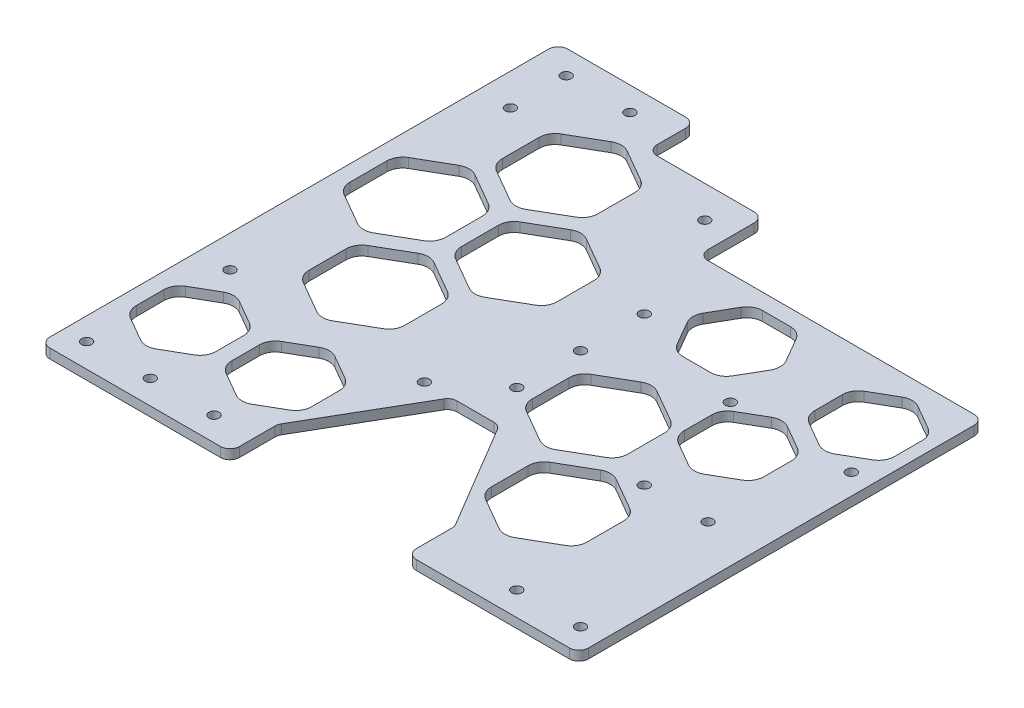
SolidWorks part; units mm, degrees
material "轻木"
ref_plane "前视基准面" through (0, 0, 0) normal (0, 0, 1) x (1, 0, 0)
ref_plane "上视基准面" through (0, 0, 0) normal (0, 1, 0) x (1, 0, 0)
ref_plane "右视基准面" through (0, 0, 0) normal (1, 0, 0) x (0, 0, -1)
other "Configuration Table"
sketch "草图1" plane through (0, 0, 0) normal (0, 1, 0) x (1, 0, 0)
  line L0 (7.5, 83.5) -> (7.5, 0) construction
  line L1 (0, 0) -> (15, 0) construction
  line L2 (0, 0) -> (0, 83.5) construction
  line L3 (0, 83.5) -> (15, 83.5) construction
  line L4 (15, 0) -> (15, 83.5) construction
  line L5 (7.5, 16) -> (7.5, 36) construction
  line L6 (0, 0) -> (0, 101) construction
  line L7 (0, 108.5) -> (-79.5, 108.5) construction
  line L8 (0, 101) -> (-79.5, 101) construction
  line L9 (0, 101) -> (0, 116) construction
  line L10 (0, 116) -> (-79.5, 116) construction
  line L11 (-79.5, 101) -> (-79.5, 116) construction
  line L12 (-33.5, 116) -> (-33.5, 101) construction
  line L13 (-36.5, 116) -> (-36.5, 101)
  line L14 (-36.5, 101) -> (0, 101)
  line L15 (0, 101) -> (0, 80.5)
  line L16 (0, 80.5) -> (15, 80.5)
  line L17 (15, 3) -> (0, 3)
  line L18 (15, 80.5) -> (45, 80.5)
  line L19 (92.5, -39) -> (0, -39) construction
  line L24 (0, 0) -> (15, 0) construction
  line L25 (0, 0) -> (0, -31.5) construction
  line L26 (0, -31.5) -> (15, -31.5) construction
  line L27 (15, 0) -> (15, -31.5) construction
  line L28 (0, -31.5) -> (92.5, -31.5) construction
  line L29 (0, -31.5) -> (0, -46.5) construction
  line L30 (0, -46.5) -> (92.5, -46.5) construction
  line L31 (92.5, -31.5) -> (92.5, -46.5) construction
  line L32 (7.5, 0) -> (7.5, -31.5) construction
  line L33 (32.5, -31.5) -> (32.5, -46.5) construction
  line L34 (35.5, -31.5) -> (35.5, -46.5)
  line L35 (89.5, -31.5) -> (89.5, -46.5)
  line L36 (89.5, -46.5) -> (35.5, -46.5)
  line L37 (15, 3) -> (35.5, -31.5)
  line L38 (89.5, -31.5) -> (89.5, 53.5)
  line L39 (89.5, 53.5) -> (155, 53.5) construction
  line L40 (-36.5, 116) -> (-79.5, 116)
  line L41 (55, 185.5) -> (142, 185.5) construction
  line L42 (55, 185.5) -> (55, 63.5) construction
  line L43 (55, 63.5) -> (142, 63.5) construction
  line L44 (142, 185.5) -> (142, 63.5) construction
  line L45 (55, 185.5) -> (142, 63.5) construction
  line L46 (55, 63.5) -> (142, 185.5) construction
  line L47 (-79.5, 116) -> (-79.5, 101)
  line L48 (-117.5, -39) -> (0, -39) construction
  line L49 (0, -31.5) -> (-117.5, -31.5) construction
  line L50 (0, -31.5) -> (0, -46.5) construction
  line L51 (0, -46.5) -> (-117.5, -46.5) construction
  line L52 (-117.5, -31.5) -> (-117.5, -46.5) construction
  line L53 (-17, -31.5) -> (-17, -46.5) construction
  line L54 (-32.5, -39) -> (-52.5, -39) construction
  line L55 (-79.5, 101) -> (-79.5, -46.5)
  line L56 (-79.5, -46.5) -> (-20, -46.5)
  line L57 (-20, -46.5) -> (-20, -31.5)
  line L58 (-20, -31.5) -> (0, 3)
  line L59 (45, 80.5) -> (45, 195.5) construction
  line L60 (45, 195.5) -> (155, 195.5) construction
  line L61 (155, 195.5) -> (155, 53.5) construction
  line L62 (61, 41.5) -> (61, 21.5) construction
  line L63 (-69.5, 91) -> (-8.5, 91) construction
  line L64 (-69.5, 91) -> (-69.5, 3) construction
  line L65 (-69.5, 3) -> (-8.5, 3) construction
  line L66 (-8.5, 91) -> (-8.5, 3) construction
  line L67 (-69.5, 91) -> (-8.5, 3) construction
  line L68 (-69.5, 3) -> (-8.5, 91) construction
  line L69 (61, 21.5) -> (25, 12.5) construction
  line L70 (25, 12.5) -> (25, 50.5) construction
  line L71 (25, 50.5) -> (61, 41.5) construction
  line L72 (89.5, 53.5) -> (89.5, 80.5)
  line L73 (89.5, 80.5) -> (45, 80.5)
  line L74 (45, 45.5) -> (54, 9.5) construction
  line L75 (54, 9.5) -> (74, 9.5) construction
  line L76 (74, 9.5) -> (83, 45.5) construction
  line L77 (83, 45.5) -> (45, 45.5) construction
  circle A0 centre (7.5, 16) radius 1.6
  circle A1 centre (7.5, 36) radius 1.6
  circle A2 centre (7.5, 56) radius 1.6
  circle A3 centre (-49.5, 108.5) radius 1.6
  circle A4 centre (-69.5, 108.5) radius 1.6
  circle A5 centre (82.5, -39) radius 1.6
  circle A6 centre (62.5, -39) radius 1.6
  circle A7 centre (-32.5, -39) radius 1.6
  circle A8 centre (-52.5, -39) radius 1.6
  circle A9 centre (-72.5, -39) radius 1.6
  circle A10 centre (-92.5, -39) radius 1.6 construction
  circle A11 centre (-112.5, -39) radius 1.6 construction
  circle A12 centre (55, 185.5) radius 1.6 construction
  circle A13 centre (142, 185.5) radius 1.6 construction
  circle A14 centre (142, 63.5) radius 1.6 construction
  circle A15 centre (55, 63.5) radius 1.6 construction
  circle A16 centre (-69.5, 91) radius 1.6
  circle A17 centre (-8.5, 91) radius 1.6
  circle A18 centre (-8.5, 3) radius 1.6
  circle A19 centre (-69.5, 3) radius 1.6
  circle A20 centre (25, 50.5) radius 1.6 construction
  circle A21 centre (61, 41.5) radius 1.6 construction
  circle A22 centre (61, 21.5) radius 1.6 construction
  circle A23 centre (25, 12.5) radius 1.6 construction
  circle A24 centre (83, 45.5) radius 1.6
  circle A25 centre (74, 9.5) radius 1.6
  circle A26 centre (54, 9.5) radius 1.6
  circle A27 centre (45, 45.5) radius 1.6
  point P53 (98.5, 124.5)
  point P85 (-39, 47)
  dimension "D3" = 16
  dimension "D6" = 3.2
  dimension "D10" = 20
  dimension "D11" = 16
  dimension "D20" = 20
  dimension "D21" = 10
  dimension "D27" = 17
  dimension "D28" = 32.5
  dimension "D1" = 15
  dimension "D2" = 83.5
  dimension "D5" = 20
  dimension "D7" = 101
  dimension "D8" = 15
  dimension "D9" = 33.5
  dimension "D12" = 10
  dimension "D13" = 3
  dimension "D14" = 3
  dimension "D15" = 3
  dimension "D16" = 46.5
  dimension "D17" = 92.5
  dimension "D18" = 17.5
  dimension "D19" = 3
  dimension "D22" = 3
  dimension "D23" = 85
  dimension "D24" = 30
  dimension "D25" = 122
  dimension "D26" = 87
  dimension "D30" = 20
  dimension "D31" = 5
  dimension "D32" = 3
  dimension "D33" = 10
  dimension "D34" = 10
  dimension "D35" = 110
  dimension "D36" = 10
  dimension "D37" = 61
  dimension "D38" = 88
  dimension "D39" = 10
  dimension "D40" = 10
  dimension "D41" = 36
  dimension "D42" = 20
  dimension "D43" = 38
  dimension "D44" = 10
  dimension "D45" = 30
  dimension "D46" = 38
  dimension "D47" = 36
  dimension "D48" = 20
  dimension "D49" = 35
  dimension "D4" = 3
  dimension "D29" = 5
extrude "凸台-拉伸1" add sketch "草图1" along normal blind 3
sketch "草图3" plane through (0, 3, 0) normal (0, 1, 0) x (1, 0, 0)
  line L1 (-112, 64.4327) -> (-97, 73.0929) construction
  line L2 (-97, 73.0929) -> (-97, 90.4134) construction
  line L3 (-97, 90.4134) -> (-112, 99.0737) construction
  line L4 (-112, 99.0737) -> (-127, 90.4134) construction
  line L5 (-127, 90.4134) -> (-127, 73.0929) construction
  line L6 (-127, 73.0929) -> (-112, 64.4327) construction
  line L8 (-112, 81.7532) -> (-104.5, 68.7628) construction
  line L9 (-77, 64.4327) -> (-62, 73.0929) construction
  line L10 (-62, 73.0929) -> (-62, 90.4134) construction
  line L11 (-62, 90.4134) -> (-77, 99.0737) construction
  line L12 (-77, 99.0737) -> (-92, 90.4134) construction
  line L13 (-92, 90.4134) -> (-92, 73.0929) construction
  line L14 (-92, 73.0929) -> (-77, 64.4327) construction
  line L15 (-42, 64.4327) -> (-27, 73.0929)
  line L16 (-27, 73.0929) -> (-27, 90.4134)
  line L17 (-27, 90.4134) -> (-42, 99.0737)
  line L18 (-42, 99.0737) -> (-57, 90.4134)
  line L19 (-57, 90.4134) -> (-57, 73.0929)
  line L20 (-57, 73.0929) -> (-42, 64.4327)
  line L21 (-7, 64.4327) -> (8, 73.0929) construction
  line L22 (8, 73.0929) -> (8, 90.4134) construction
  line L23 (8, 90.4134) -> (-7, 99.0737) construction
  line L24 (-7, 99.0737) -> (-22, 90.4134) construction
  line L25 (-22, 90.4134) -> (-22, 73.0929) construction
  line L26 (-22, 73.0929) -> (-7, 64.4327) construction
  line L27 (28, 64.4327) -> (43, 73.0929) construction
  line L28 (43, 73.0929) -> (43, 90.4134) construction
  line L29 (43, 90.4134) -> (28, 99.0737) construction
  line L30 (28, 99.0737) -> (13, 90.4134) construction
  line L31 (13, 90.4134) -> (13, 73.0929) construction
  line L32 (13, 73.0929) -> (28, 64.4327) construction
  line L33 (63, 64.4327) -> (78, 73.0929) construction
  line L34 (78, 73.0929) -> (78, 90.4134) construction
  line L35 (78, 90.4134) -> (63, 99.0737) construction
  line L36 (63, 99.0737) -> (48, 90.4134) construction
  line L37 (48, 90.4134) -> (48, 73.0929) construction
  line L38 (48, 73.0929) -> (63, 64.4327) construction
  line L39 (-59.5, 34.1218) -> (-44.5, 42.782)
  line L40 (-44.5, 42.782) -> (-44.5, 60.1025)
  line L41 (-44.5, 60.1025) -> (-59.5, 68.7628)
  line L42 (-59.5, 68.7628) -> (-74.5, 60.1025)
  line L43 (-74.5, 60.1025) -> (-74.5, 42.782)
  line L44 (-74.5, 42.782) -> (-59.5, 34.1218)
  line L45 (-24.5, 34.1218) -> (-9.5, 42.782)
  line L46 (-9.5, 42.782) -> (-9.5, 60.1025)
  line L47 (-9.5, 60.1025) -> (-24.5, 68.7628)
  line L48 (-24.5, 68.7628) -> (-39.5, 60.1025)
  line L49 (-39.5, 60.1025) -> (-39.5, 42.782)
  line L50 (-39.5, 42.782) -> (-24.5, 34.1218)
  line L51 (10.5, 34.1218) -> (25.5, 42.782) construction
  line L52 (25.5, 42.782) -> (25.5, 60.1025) construction
  line L53 (25.5, 60.1025) -> (10.5, 68.7628) construction
  line L54 (10.5, 68.7628) -> (-4.5, 60.1025) construction
  line L55 (-4.5, 60.1025) -> (-4.5, 42.782) construction
  line L56 (-4.5, 42.782) -> (10.5, 34.1218) construction
  line L57 (45.5, 34.1218) -> (60.5, 42.782) construction
  line L58 (60.5, 42.782) -> (60.5, 60.1025) construction
  line L59 (60.5, 60.1025) -> (45.5, 68.7628) construction
  line L60 (45.5, 68.7628) -> (30.5, 60.1025) construction
  line L61 (30.5, 60.1025) -> (30.5, 42.782) construction
  line L62 (30.5, 42.782) -> (45.5, 34.1218) construction
  line L63 (80.5, 34.1218) -> (95.5, 42.782) construction
  line L64 (95.5, 42.782) -> (95.5, 60.1025) construction
  line L65 (95.5, 60.1025) -> (80.5, 68.7628) construction
  line L66 (80.5, 68.7628) -> (65.5, 60.1025) construction
  line L67 (65.5, 60.1025) -> (65.5, 42.782) construction
  line L68 (65.5, 42.782) -> (80.5, 34.1218) construction
  line L69 (-42, 3.8109) -> (-27, 12.4711)
  line L70 (-27, 12.4711) -> (-27, 29.7917)
  line L71 (-27, 29.7917) -> (-42, 38.4519)
  line L72 (-42, 38.4519) -> (-57, 29.7917)
  line L73 (-57, 29.7917) -> (-57, 12.4711)
  line L74 (-57, 12.4711) -> (-42, 3.8109)
  line L75 (-7, 3.8109) -> (8, 12.4711) construction
  line L76 (8, 12.4711) -> (8, 29.7917) construction
  line L77 (8, 29.7917) -> (-7, 38.4519) construction
  line L78 (-7, 38.4519) -> (-22, 29.7917) construction
  line L79 (-22, 29.7917) -> (-22, 12.4711) construction
  line L80 (-22, 12.4711) -> (-7, 3.8109) construction
  line L81 (28, 3.8109) -> (43, 12.4711)
  line L82 (43, 12.4711) -> (43, 29.7917)
  line L83 (43, 29.7917) -> (28, 38.4519)
  line L84 (28, 38.4519) -> (13, 29.7917)
  line L85 (13, 29.7917) -> (13, 12.4711)
  line L86 (13, 12.4711) -> (28, 3.8109)
  line L87 (63, 3.8109) -> (78, 12.4711) construction
  line L88 (78, 12.4711) -> (78, 29.7917) construction
  line L89 (78, 29.7917) -> (63, 38.4519) construction
  line L90 (63, 38.4519) -> (48, 29.7917) construction
  line L91 (48, 29.7917) -> (48, 12.4711) construction
  line L92 (48, 12.4711) -> (63, 3.8109) construction
  line L93 (98, 3.8109) -> (113, 12.4711) construction
  line L94 (113, 12.4711) -> (113, 29.7917) construction
  line L95 (113, 29.7917) -> (98, 38.4519) construction
  line L96 (98, 38.4519) -> (83, 29.7917) construction
  line L97 (83, 29.7917) -> (83, 12.4711) construction
  line L98 (83, 12.4711) -> (98, 3.8109) construction
  line L99 (-24.5, -26.5) -> (-9.5, -17.8397) construction
  line L100 (-9.5, -17.8397) -> (-9.5, -0.5192) construction
  line L101 (-9.5, -0.5192) -> (-24.5, 8.141) construction
  line L102 (-24.5, 8.141) -> (-39.5, -0.5192) construction
  line L103 (-39.5, -0.5192) -> (-39.5, -17.8397) construction
  line L104 (-39.5, -17.8397) -> (-24.5, -26.5) construction
  line L105 (10.5, -26.5) -> (25.5, -17.8397) construction
  line L106 (25.5, -17.8397) -> (25.5, -0.5192) construction
  line L107 (25.5, -0.5192) -> (10.5, 8.141) construction
  line L108 (10.5, 8.141) -> (-4.5, -0.5192) construction
  line L109 (-4.5, -0.5192) -> (-4.5, -17.8397) construction
  line L110 (-4.5, -17.8397) -> (10.5, -26.5) construction
  line L111 (45.5, -26.5) -> (60.5, -17.8397)
  line L112 (60.5, -17.8397) -> (60.5, -0.5192)
  line L113 (60.5, -0.5192) -> (45.5, 8.141)
  line L114 (45.5, 8.141) -> (30.5, -0.5192)
  line L115 (30.5, -0.5192) -> (30.5, -17.8397)
  line L116 (30.5, -17.8397) -> (45.5, -26.5)
  line L117 (80.5, -26.5) -> (95.5, -17.8397) construction
  line L118 (95.5, -17.8397) -> (95.5, -0.5192) construction
  line L119 (95.5, -0.5192) -> (80.5, 8.141) construction
  line L120 (80.5, 8.141) -> (65.5, -0.5192) construction
  line L121 (65.5, -0.5192) -> (65.5, -17.8397) construction
  line L122 (65.5, -17.8397) -> (80.5, -26.5) construction
  line L123 (115.5, -26.5) -> (130.5, -17.8397) construction
  line L124 (130.5, -17.8397) -> (130.5, -0.5192) construction
  line L125 (130.5, -0.5192) -> (115.5, 8.141) construction
  line L126 (115.5, 8.141) -> (100.5, -0.5192) construction
  line L127 (100.5, -0.5192) -> (100.5, -17.8397) construction
  line L128 (100.5, -17.8397) -> (115.5, -26.5) construction
  line L129 (-94.5, 34.1218) -> (-79.5, 42.782) construction
  line L130 (-79.5, 42.782) -> (-79.5, 60.1025) construction
  line L131 (-79.5, 60.1025) -> (-94.5, 68.7628) construction
  line L132 (-94.5, 68.7628) -> (-109.5, 60.1025) construction
  line L133 (-109.5, 60.1025) -> (-109.5, 42.782) construction
  line L134 (-109.5, 42.782) -> (-94.5, 34.1218) construction
  line L135 (-77, 3.8109) -> (-62, 12.4711) construction
  line L136 (-62, 12.4711) -> (-62, 29.7917) construction
  line L137 (-62, 29.7917) -> (-77, 38.4519) construction
  line L138 (-77, 38.4519) -> (-92, 29.7917) construction
  line L139 (-92, 29.7917) -> (-92, 12.4711) construction
  line L140 (-92, 12.4711) -> (-77, 3.8109) construction
  line L141 (-59.5, -26.5) -> (-44.5, -17.8397) construction
  line L142 (-44.5, -17.8397) -> (-44.5, -0.5192) construction
  line L143 (-44.5, -0.5192) -> (-59.5, 8.141) construction
  line L144 (-59.5, 8.141) -> (-74.5, -0.5192) construction
  line L145 (-74.5, -0.5192) -> (-74.5, -17.8397) construction
  line L146 (-74.5, -17.8397) -> (-59.5, -26.5) construction
  line L147 (-112, 64.4327) -> (-77, 64.4327) construction
  line L148 (-112, 64.4327) -> (-94.5, 34.1218) construction
  line L149 (-79.5, 116) -> (-79.5, -46.5) construction
  circle A0 centre (-112, 81.7532) radius 15 construction
  dimension "D1" = 30
  dimension "D2" = 5
  dimension "D3" = 5
  dimension "D6" = 35
  dimension "D7" = 35
  dimension "D8" = 22.5
  dimension "D4" = 6
  dimension "D5" = 4
extrude "切除-拉伸1" cut sketch "草图3" against normal blind 7
sketch "草图4" plane through (0, 3, 0) normal (0, 1, 0) x (1, 0, 0)
  line L0 (-62, -17.0662) -> (-55.75, -6.2409) construction
  line L1 (-62, -2.6325) -> (-74.5, -9.8494)
  line L2 (-74.5, -9.8494) -> (-74.5, -24.2831)
  line L3 (-74.5, -24.2831) -> (-62, -31.5)
  line L4 (-62, -31.5) -> (-49.5, -24.2831)
  line L5 (-49.5, -24.2831) -> (-49.5, -9.8494)
  line L6 (-49.5, -9.8494) -> (-62, -2.6325)
  line L7 (-79.5, 116) -> (-79.5, -46.5) construction
  line L8 (-79.5, -46.5) -> (-20, -46.5) construction
  line L9 (-32, -2.6325) -> (-44.5, -9.8494)
  line L10 (-44.5, -9.8494) -> (-44.5, -24.2831)
  line L11 (-44.5, -24.2831) -> (-32, -31.5)
  line L12 (-32, -31.5) -> (-19.5, -24.2831)
  line L13 (-19.5, -24.2831) -> (-19.5, -9.8494)
  line L14 (-19.5, -9.8494) -> (-32, -2.6325)
  line L15 (-2, -2.6325) -> (-14.5, -9.8494) construction
  line L16 (-14.5, -9.8494) -> (-14.5, -24.2831) construction
  line L17 (-14.5, -24.2831) -> (-2, -31.5) construction
  line L18 (-2, -31.5) -> (10.5, -24.2831) construction
  line L19 (10.5, -24.2831) -> (10.5, -9.8494) construction
  line L20 (10.5, -9.8494) -> (-2, -2.6325) construction
  line L21 (28, -2.6325) -> (15.5, -9.8494) construction
  line L22 (15.5, -9.8494) -> (15.5, -24.2831) construction
  line L23 (15.5, -24.2831) -> (28, -31.5) construction
  line L24 (28, -31.5) -> (40.5, -24.2831) construction
  line L25 (40.5, -24.2831) -> (40.5, -9.8494) construction
  line L26 (40.5, -9.8494) -> (28, -2.6325) construction
  line L27 (58, -2.6325) -> (45.5, -9.8494) construction
  line L28 (45.5, -9.8494) -> (45.5, -24.2831) construction
  line L29 (45.5, -24.2831) -> (58, -31.5) construction
  line L30 (58, -31.5) -> (70.5, -24.2831) construction
  line L31 (70.5, -24.2831) -> (70.5, -9.8494) construction
  line L32 (70.5, -9.8494) -> (58, -2.6325) construction
  line L33 (-17, 23.3483) -> (-29.5, 16.1314) construction
  line L34 (-29.5, 16.1314) -> (-29.5, 1.6976) construction
  line L35 (-29.5, 1.6976) -> (-17, -5.5192) construction
  line L36 (-17, -5.5192) -> (-4.5, 1.6976) construction
  line L37 (-4.5, 1.6976) -> (-4.5, 16.1314) construction
  line L38 (-4.5, 16.1314) -> (-17, 23.3483) construction
  line L39 (13, 23.3483) -> (0.5, 16.1314) construction
  line L40 (0.5, 16.1314) -> (0.5, 1.6976) construction
  line L41 (0.5, 1.6976) -> (13, -5.5192) construction
  line L42 (13, -5.5192) -> (25.5, 1.6976) construction
  line L43 (25.5, 1.6976) -> (25.5, 16.1314) construction
  line L44 (25.5, 16.1314) -> (13, 23.3483) construction
  line L45 (43, 23.3483) -> (30.5, 16.1314) construction
  line L46 (30.5, 16.1314) -> (30.5, 1.6976) construction
  line L47 (30.5, 1.6976) -> (43, -5.5192) construction
  line L48 (43, -5.5192) -> (55.5, 1.6976) construction
  line L49 (55.5, 1.6976) -> (55.5, 16.1314) construction
  line L50 (55.5, 16.1314) -> (43, 23.3483) construction
  line L51 (73, 23.3483) -> (60.5, 16.1314) construction
  line L52 (60.5, 16.1314) -> (60.5, 1.6976) construction
  line L53 (60.5, 1.6976) -> (73, -5.5192) construction
  line L54 (73, -5.5192) -> (85.5, 1.6976) construction
  line L55 (85.5, 1.6976) -> (85.5, 16.1314) construction
  line L56 (85.5, 16.1314) -> (73, 23.3483) construction
  line L57 (-2, 49.329) -> (-14.5, 42.1122) construction
  line L58 (-14.5, 42.1122) -> (-14.5, 27.6784) construction
  line L59 (-14.5, 27.6784) -> (-2, 20.4615) construction
  line L60 (-2, 20.4615) -> (10.5, 27.6784) construction
  line L61 (10.5, 27.6784) -> (10.5, 42.1122) construction
  line L62 (10.5, 42.1122) -> (-2, 49.329) construction
  line L63 (28, 49.329) -> (15.5, 42.1122) construction
  line L64 (15.5, 42.1122) -> (15.5, 27.6784) construction
  line L65 (15.5, 27.6784) -> (28, 20.4615) construction
  line L66 (28, 20.4615) -> (40.5, 27.6784) construction
  line L67 (40.5, 27.6784) -> (40.5, 42.1122) construction
  line L68 (40.5, 42.1122) -> (28, 49.329) construction
  line L69 (58, 49.329) -> (45.5, 42.1122)
  line L70 (45.5, 42.1122) -> (45.5, 27.6784)
  line L71 (45.5, 27.6784) -> (58, 20.4615)
  line L72 (58, 20.4615) -> (70.5, 27.6784)
  line L73 (70.5, 27.6784) -> (70.5, 42.1122)
  line L74 (70.5, 42.1122) -> (58, 49.329)
  line L75 (88, 49.329) -> (75.5, 42.1122) construction
  line L76 (75.5, 42.1122) -> (75.5, 27.6784) construction
  line L77 (75.5, 27.6784) -> (88, 20.4615) construction
  line L78 (88, 20.4615) -> (100.5, 27.6784) construction
  line L79 (100.5, 27.6784) -> (100.5, 42.1122) construction
  line L80 (100.5, 42.1122) -> (88, 49.329) construction
  line L81 (13, 75.3098) -> (0.5, 68.0929) construction
  line L82 (0.5, 68.0929) -> (0.5, 53.6592) construction
  line L83 (0.5, 53.6592) -> (13, 46.4423) construction
  line L84 (13, 46.4423) -> (25.5, 53.6592) construction
  line L85 (25.5, 53.6592) -> (25.5, 68.0929) construction
  line L86 (25.5, 68.0929) -> (13, 75.3098) construction
  line L87 (43, 75.3098) -> (30.5, 68.0929) construction
  line L88 (30.5, 68.0929) -> (30.5, 53.6592) construction
  line L89 (30.5, 53.6592) -> (43, 46.4423) construction
  line L90 (43, 46.4423) -> (55.5, 53.6592) construction
  line L91 (55.5, 53.6592) -> (55.5, 68.0929) construction
  line L92 (55.5, 68.0929) -> (43, 75.3098) construction
  line L93 (73, 75.3098) -> (60.5, 68.0929)
  line L94 (60.5, 68.0929) -> (60.5, 53.6592)
  line L95 (60.5, 53.6592) -> (73, 46.4423)
  line L96 (73, 46.4423) -> (85.5, 53.6592)
  line L97 (85.5, 53.6592) -> (85.5, 68.0929)
  line L98 (85.5, 68.0929) -> (73, 75.3098)
  line L99 (103, 75.3098) -> (90.5, 68.0929) construction
  line L100 (90.5, 68.0929) -> (90.5, 53.6592) construction
  line L101 (90.5, 53.6592) -> (103, 46.4423) construction
  line L102 (103, 46.4423) -> (115.5, 53.6592) construction
  line L103 (115.5, 53.6592) -> (115.5, 68.0929) construction
  line L104 (115.5, 68.0929) -> (103, 75.3098) construction
  line L105 (28, 101.2906) -> (15.5, 94.0737) construction
  line L106 (15.5, 94.0737) -> (15.5, 79.6399) construction
  line L107 (15.5, 79.6399) -> (28, 72.423) construction
  line L108 (28, 72.423) -> (40.5, 79.6399) construction
  line L109 (40.5, 79.6399) -> (40.5, 94.0737) construction
  line L110 (40.5, 94.0737) -> (28, 101.2906) construction
  line L111 (58, 101.2906) -> (45.5, 94.0737) construction
  line L112 (45.5, 94.0737) -> (45.5, 79.6399) construction
  line L113 (45.5, 79.6399) -> (58, 72.423) construction
  line L114 (58, 72.423) -> (70.5, 79.6399) construction
  line L115 (70.5, 79.6399) -> (70.5, 94.0737) construction
  line L116 (70.5, 94.0737) -> (58, 101.2906) construction
  line L117 (88, 101.2906) -> (75.5, 94.0737) construction
  line L118 (75.5, 94.0737) -> (75.5, 79.6399) construction
  line L119 (75.5, 79.6399) -> (88, 72.423) construction
  line L120 (88, 72.423) -> (100.5, 79.6399) construction
  line L121 (100.5, 79.6399) -> (100.5, 94.0737) construction
  line L122 (100.5, 94.0737) -> (88, 101.2906) construction
  line L123 (118, 101.2906) -> (105.5, 94.0737) construction
  line L124 (105.5, 94.0737) -> (105.5, 79.6399) construction
  line L125 (105.5, 79.6399) -> (118, 72.423) construction
  line L126 (118, 72.423) -> (130.5, 79.6399) construction
  line L127 (130.5, 79.6399) -> (130.5, 94.0737) construction
  line L128 (130.5, 94.0737) -> (118, 101.2906) construction
  line L129 (-47, 23.3483) -> (-59.5, 16.1314) construction
  line L130 (-59.5, 16.1314) -> (-59.5, 1.6976) construction
  line L131 (-59.5, 1.6976) -> (-47, -5.5192) construction
  line L132 (-47, -5.5192) -> (-34.5, 1.6976) construction
  line L133 (-34.5, 1.6976) -> (-34.5, 16.1314) construction
  line L134 (-34.5, 16.1314) -> (-47, 23.3483) construction
  line L135 (-32, 49.329) -> (-44.5, 42.1122) construction
  line L136 (-44.5, 42.1122) -> (-44.5, 27.6784) construction
  line L137 (-44.5, 27.6784) -> (-32, 20.4615) construction
  line L138 (-32, 20.4615) -> (-19.5, 27.6784) construction
  line L139 (-19.5, 27.6784) -> (-19.5, 42.1122) construction
  line L140 (-19.5, 42.1122) -> (-32, 49.329) construction
  line L141 (-17, 75.3098) -> (-29.5, 68.0929) construction
  line L142 (-29.5, 68.0929) -> (-29.5, 53.6592) construction
  line L143 (-29.5, 53.6592) -> (-17, 46.4423) construction
  line L144 (-17, 46.4423) -> (-4.5, 53.6592) construction
  line L145 (-4.5, 53.6592) -> (-4.5, 68.0929) construction
  line L146 (-4.5, 68.0929) -> (-17, 75.3098) construction
  line L147 (-2, 101.2906) -> (-14.5, 94.0737) construction
  line L148 (-14.5, 94.0737) -> (-14.5, 79.6399) construction
  line L149 (-14.5, 79.6399) -> (-2, 72.423) construction
  line L150 (-2, 72.423) -> (10.5, 79.6399) construction
  line L151 (10.5, 79.6399) -> (10.5, 94.0737) construction
  line L152 (10.5, 94.0737) -> (-2, 101.2906) construction
  line L153 (-62, -2.6325) -> (-32, -2.6325) construction
  line L154 (-62, -2.6325) -> (-47, 23.3483) construction
  circle A0 centre (-62, -17.0662) radius 12.5 construction
  dimension "D1" = 25
  dimension "D2" = 5
  dimension "D3" = 15
  dimension "D6" = 30
  dimension "D7" = 30
  dimension "D4" = 5
  dimension "D5" = 5
extrude "切除-拉伸2" cut sketch "草图4" against normal through all
sketch "草图5" plane through (0, 3, 0) normal (0, 1, 0) x (1, 0, 0)
  line L7 (89.5, 80.5) -> (0, 80.5) construction
  line L8 (43.9338, 63) -> (36.7169, 75.5)
  line L9 (36.7169, 75.5) -> (22.2831, 75.5)
  line L10 (22.2831, 75.5) -> (15.0662, 63)
  line L11 (15.0662, 63) -> (22.2831, 50.5)
  line L12 (22.2831, 50.5) -> (36.7169, 50.5)
  line L13 (36.7169, 50.5) -> (43.9338, 63)
  line L14 (89.5, -46.5) -> (89.5, 80.5) construction
  circle A0 centre (29.5, 63) radius 12.5 construction
  dimension "D1" = 25
  dimension "D2" = 5
  dimension "D3" = 60
extrude "切除-拉伸3" cut sketch "草图5" against normal blind 10
fillet "圆角2" radius 5 66 edges at (-57, 1.5, -90.4134) (-27, 1.5, -90.4134) (-27, 1.5, -73.0929) (-42, 1.5, -64.4327) (-57, 1.5, -73.0929) (30.5, 1.5, 0.5192) (45.5, 1.5, -8.141) (60.5, 1.5, 0.5192) (60.5, 1.5, 17.8397) (45.5, 1.5, 26.5) (30.5, 1.5, 17.8397) (-57, 1.5, -29.7917) (-42, 1.5, -38.4519) (-27, 1.5, -29.7917) (-27, 1.5, -12.4711) (-42, 1.5, -3.8109) (-57, 1.5, -12.4711) (-39.5, 1.5, -60.1025) (-24.5, 1.5, -68.7628) (-9.5, 1.5, -60.1025) (-9.5, 1.5, -42.782) (-24.5, 1.5, -34.1218) (-39.5, 1.5, -42.782) (-74.5, 1.5, -60.1025) (-59.5, 1.5, -68.7628) (-44.5, 1.5, -60.1025) (-44.5, 1.5, -42.782) (-59.5, 1.5, -34.1218) (-74.5, 1.5, -42.782) (-19.5, 1.5, 24.2831) (-32, 1.5, 31.5) (-44.5, 1.5, 24.2831) (-44.5, 1.5, 9.8494) (-32, 1.5, 2.6325) (-19.5, 1.5, 9.8494) (85.5, 1.5, -53.6592) (73, 1.5, -46.4423) (60.5, 1.5, -53.6592) (60.5, 1.5, -68.0929) (73, 1.5, -75.3098) (85.5, 1.5, -68.0929) (-49.5, 1.5, 24.2831) (-62, 1.5, 31.5) (-74.5, 1.5, 24.2831) (-74.5, 1.5, 9.8494) (-62, 1.5, 2.6325) (-49.5, 1.5, 9.8494) (-42, 1.5, -99.0737) (13, 1.5, -29.7917) (28, 1.5, -38.4519) (43, 1.5, -29.7917) (43, 1.5, -12.4711) (28, 1.5, -3.8109) (13, 1.5, -12.4711) (70.5, 1.5, -27.6784) (58, 1.5, -20.4615) (45.5, 1.5, -27.6784) (45.5, 1.5, -42.1122) (58, 1.5, -49.329) (70.5, 1.5, -42.1122) (22.2831, 1.5, -50.5) (15.0662, 1.5, -63) (36.7169, 1.5, -75.5) (43.9338, 1.5, -63) (36.7169, 1.5, -50.5) (22.2831, 1.5, -75.5)
fillet "圆角1" radius 3 14 edges at (-79.5, 1.5, -116) (-36.5, 1.5, -116) (-36.5, 1.5, -101) (0, 1.5, -101) (89.5, 1.5, -80.5) (89.5, 1.5, 46.5) (35.5, 1.5, 46.5) (35.5, 1.5, 31.5) (15, 1.5, -3) (0, 1.5, -3) (-20, 1.5, 31.5) (-20, 1.5, 46.5) (-79.5, 1.5, 46.5) (0, 1.5, -80.5)
